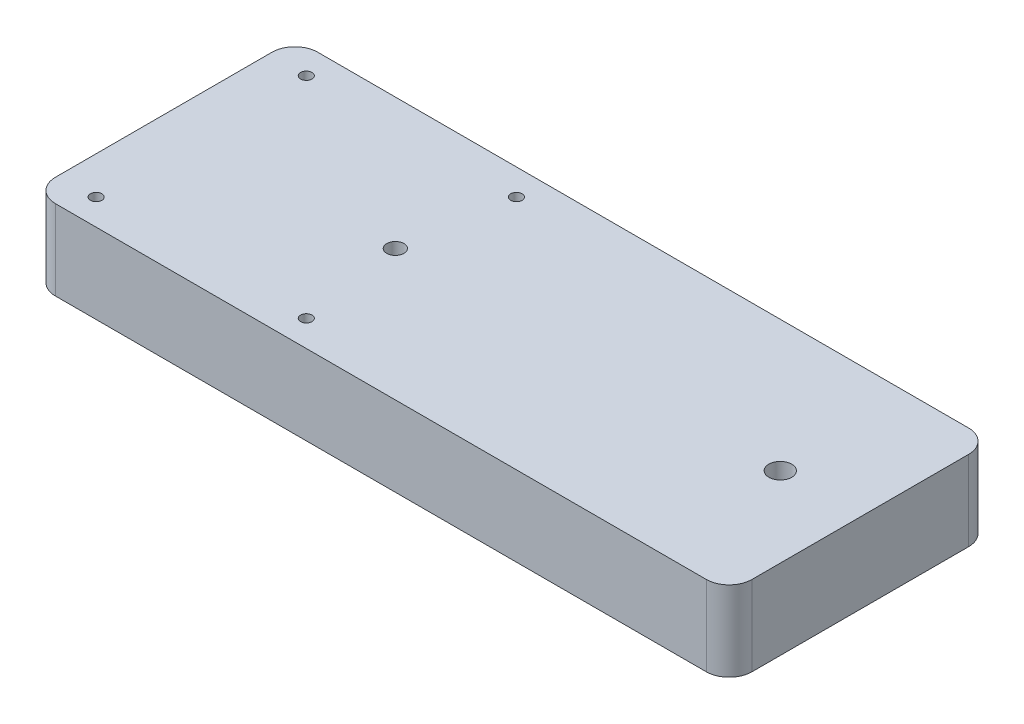
SolidWorks part; units mm, degrees
ref_plane "Front Plane" through (0, 0, 0) normal (0, 0, 1) x (1, 0, 0)
ref_plane "Top Plane" through (0, 0, 0) normal (0, 1, 0) x (1, 0, 0)
ref_plane "Right Plane" through (0, 0, 0) normal (1, 0, 0) x (0, 0, -1)
sketch "Sketch1" plane through (0, 0, 0) normal (0, 1, 0) x (1, 0, 0)
  line L0 (0, 0) -> (45.9619, 45.9619) construction
  line L1 (0, 0) -> (45.9619, -45.9619) construction
  line L2 (0, 0) -> (-45.9619, -45.9619) construction
  line L3 (0, 0) -> (-45.9619, 45.9619) construction
  line L4 (0, 25) -> (0, -25) construction
  line L6 (-52.3814, 57.3814) -> (62.3814, 57.3814)
  line L7 (-62.3814, 47.3814) -> (-62.3814, -47.3814)
  line L8 (-52.3814, -57.3814) -> (62.3814, -57.3814)
  line L9 (62.3814, 57.3814) -> (62.3814, -57.3814) construction
  line L10 (-62.3814, 57.3814) -> (62.3814, -57.3814) construction
  line L11 (-62.3814, -57.3814) -> (62.3814, 57.3814) construction
  line L12 (62.3814, 57.3814) -> (232.3814, 57.3814)
  line L13 (62.3814, 57.3814) -> (62.3814, -57.3814) construction
  line L14 (62.3814, -57.3814) -> (232.3814, -57.3814)
  line L15 (242.3814, 47.3814) -> (242.3814, -47.3814)
  arc A0 (-52.3814, 57.3814) -> (-62.3814, 47.3814) centre (-52.3814, 47.3814) ccw
  arc A1 (-62.3814, -47.3814) -> (-52.3814, -57.3814) centre (-52.3814, -47.3814) ccw
  arc A2 (232.3814, -57.3814) -> (242.3814, -47.3814) centre (232.3814, -47.3814) ccw
  arc A3 (232.3814, 57.3814) -> (242.3814, 47.3814) centre (232.3814, 47.3814) cw
  point P5 (0, 0)
  point P23 (242.3814, -57.3814)
  dimension "D7" = 10
  dimension "D1" = 65
  dimension "D3" = 50
  dimension "D4" = 45
  dimension "D5" = 20
  dimension "D8" = 114.7627
  dimension "D6" = 180
  dimension "D2" = 4
extrude "Boss-Extrude1" add sketch "Sketch1" along normal blind 35
sketch "Sketch2" plane through (0, 35, 0) normal (0, 1, 0) x (1, 0, 0)
  line L0 (242.3814, -47.3814) -> (242.3814, 47.3814) construction
  circle A0 centre (207.3814, 0) radius 5
  dimension "D1" = 10
  dimension "D2" = 35
extrude "Cut-Extrude1" cut sketch "Sketch2" against normal up to surface (35 mm away) up to face at (90, 0, 0)
sketch "Sketch3" plane through (0, 35, 0) normal (0, 1, 0) x (1, 0, 0)
  line L0 (0, 50) -> (0, -50) construction
  line L1 (0, 0) -> (45.9619, 45.9619) construction
  line L2 (-45.9619, 45.9619) -> (0, 0) construction
  circle A0 centre (45.9619, 45.9619) radius 2.5
  circle A1 centre (45.9619, -45.9619) radius 2.5
  circle A2 centre (-45.9619, -45.9619) radius 2.5
  circle A3 centre (-45.9619, 45.9619) radius 2.5
  circle A4 centre (38.9619, 0) radius 3.75
  point P4 (0, 0)
  dimension "D1" = 65
  dimension "D3" = 5
  dimension "D6" = 7.5
  dimension "D2" = 45
  dimension "D5" = 90
  dimension "D7" = 7
  dimension "D4" = 4
extrude "Cut-Extrude2" cut sketch "Sketch3" against normal through all
equation "\"Platform Diameter\"= 150mm'Used in J1"
equation "\"Platform Thickness\"= 10mm"
equation "\"Guide Rod Diameter\"= 5mm'Used in J1"
equation "\"Elevator Height\" = 220mm"
equation "\"Top Thickness\"= 5mm"
equation "\"Guide Rod Length\"= \"Elevator Height\" - \"Platform Thickness\" - \"Top Thickness\""
equation "\"Elevator Screw Diameter\"= 7.5mm"
equation "\"Guide Rod Offset\"= 10mm"
equation "\"D1@Sketch1\"=(\"Platform Diameter\"/2) - \"Guide Rod Offset\""
equation "\"Length from Elevator\"= 180mm"
equation "\"Thickness of Segment\"= 35mm"
equation "\"D6@Sketch1\"=\"Length from Elevator\""
equation "\"D1@Boss-Extrude1\"=\"Thickness of Segment\""
equation "\"D3@Sketch3\"=\"Guide Rod Diameter\""
equation "\"D1@Sketch3\"=(\"Platform Diameter\"/2) - \"Guide Rod Offset\""
equation "\"D6@Sketch3\"=\"Elevator Screw Diameter\""
